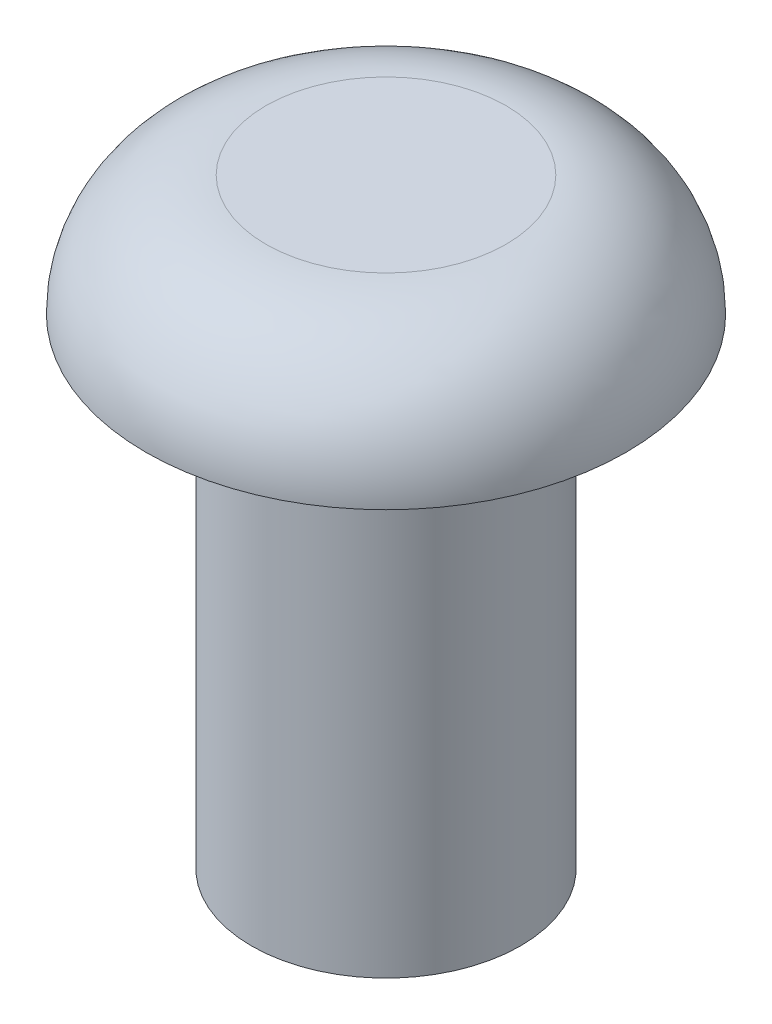
SolidWorks part; units mm, degrees
material "AISI 316 Annealed Stainless Steel Bar (SS)"
ref_plane "Front Plane" through (0, 0, 0) normal (0, 0, 1) x (1, 0, 0)
ref_plane "Top Plane" through (0, 0, 0) normal (0, 1, 0) x (1, 0, 0)
ref_plane "Right Plane" through (0, 0, 0) normal (1, 0, 0) x (0, 0, -1)
sketch "Sketch1" plane through (0, 0, 0) normal (1, 0, 0) x (0, 0, -1)
  line L0 (0, 0) -> (0, 4.7969) construction
  line L1 (0, 0) -> (1.778, 0)
  line L2 (1.778, 0) -> (1.778, 6.35)
  line L3 (1.778, 6.35) -> (3.175, 6.35)
  line L4 (0, 7.9375) -> (1.5875, 7.9375)
  line L5 (0, 7.9375) -> (0, 0)
  arc A0 (1.5875, 7.9375) -> (3.175, 6.35) centre (1.5875, 6.35) cw
  dimension "D1" = 3.556
  dimension "D2" = 6.35
  dimension "D3" = 6.35
  dimension "D4" = 3.175
  dimension "D5" = 1.5875
revolve "Revolve1" add sketch "Sketch1" angle 360 about L0
fillet "Fillet1" [suppressed] radius 0.381
